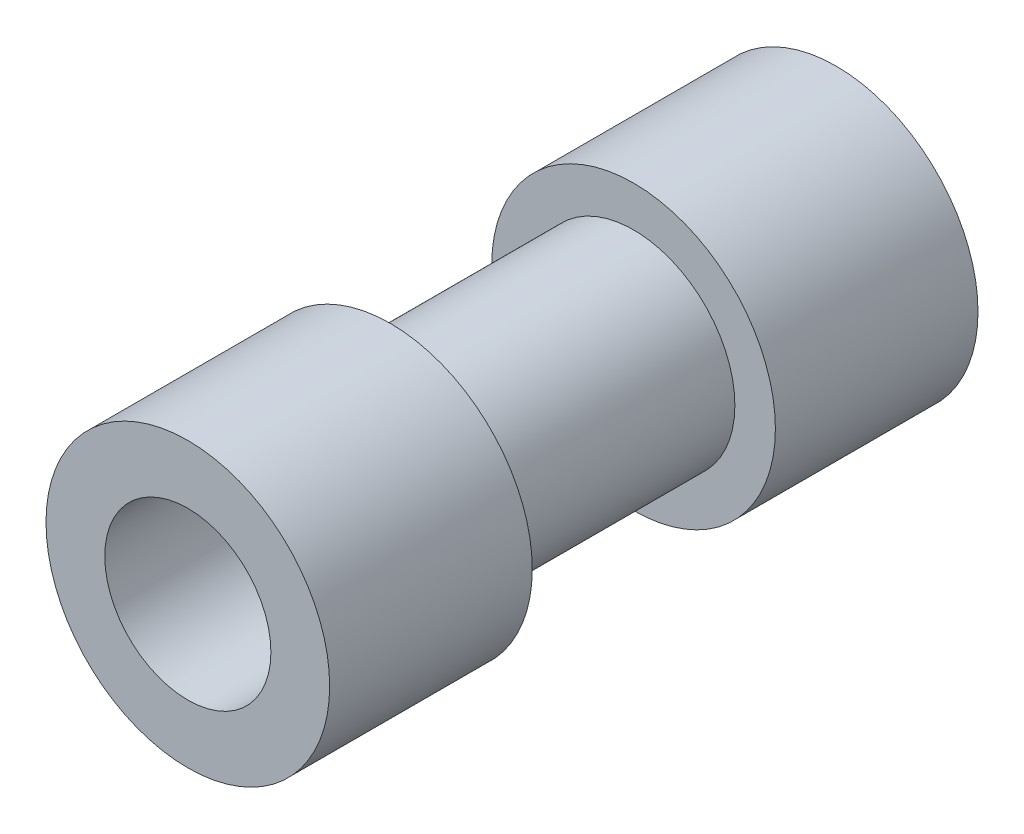
SolidWorks part; units mm, degrees
material "H62"
ref_plane "前视基准面" through (0, 0, 0) normal (0, 0, 1) x (1, 0, 0)
ref_plane "上视基准面" through (0, 0, 0) normal (0, 1, 0) x (1, 0, 0)
ref_plane "右视基准面" through (0, 0, 0) normal (1, 0, 0) x (0, 0, -1)
other "Configuration Table"
sketch "草图1" plane through (0, 0, 0) normal (0, 0, 1) x (1, 0, 0)
  circle A0 centre (0, 0) radius 1.75
  dimension "D1" = 3.5
extrude "凸台-拉伸1" add sketch "草图1" along normal blind 2.5
sketch "草图2" plane through (0, 0, 2.5) normal (0, 0, 1) x (1, 0, 0)
  circle A0 centre (0, 0) radius 1.25
  circle A1 centre (0, 0) radius 1.75 construction
  dimension "D1" = 0.5
extrude "凸台-拉伸2" add sketch "草图2" along normal blind 3
sketch "草图3" plane through (0, 0, 5.5) normal (0, 0, 1) x (1, 0, 0)
  circle A1 centre (0, 0) radius 1.75
  circle A2 centre (0, 0) radius 1.75
  dimension "D1" = 0
extrude "凸台-拉伸3" add sketch "草图3" along normal blind 2.5
hole_wizard "M2.5 螺纹孔1" positions "草图4" profile "草图5" tap size "M2.5" standard "GB" end condition through all
sketch "草图4" plane through (0, 0, 8) normal (0, 0, 1) x (1, 0, 0)
  point P0 (0, 0)
sketch "草图5" plane through (0, 0, 8) normal (1, 0, 0) x (0, -1, 0)
  line L0 (0, 0) -> (0, 8)
  line L1 (0, 8) -> (1.025, 8)
  line L2 (1.025, 8) -> (1.025, 0)
  line L5 (1.025, 0) -> (0, 0)
  line L11 (0, -6.35) -> (0, 107.95) construction
  dimension "通孔螺纹孔钻头直径" = 2.05
  dimension "通孔螺纹孔钻头深度" = 8
cosmetic thread "孔螺蚊线1"
